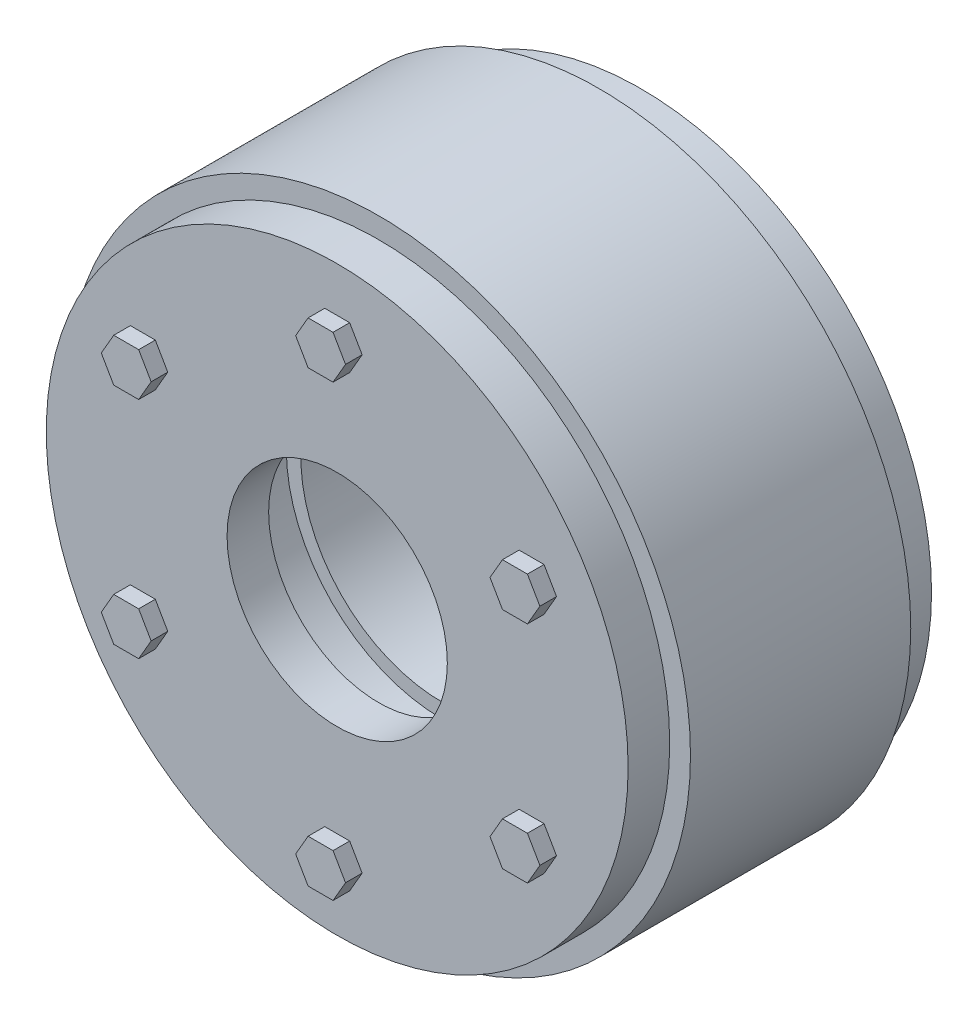
SolidWorks part; units mm, degrees
ref_plane "前视基准面" through (0, 0, 0) normal (0, 0, 1) x (1, 0, 0)
ref_plane "上视基准面" through (0, 0, 0) normal (0, 1, 0) x (1, 0, 0)
ref_plane "右视基准面" through (0, 0, 0) normal (1, 0, 0) x (0, 0, -1)
sketch "草图1" plane through (0, 0, 0) normal (0, 1, 0) x (1, 0, 0)
  line L0 (37.5, 26.5) -> (37.5, 11.25)
  line L1 (37.5, 11.25) -> (34, 11.25)
  line L2 (34, 11.25) -> (34, -11.25)
  line L3 (34, -11.25) -> (37.5, -11.25)
  line L4 (37.5, -11.25) -> (37.5, -26.5)
  line L5 (37.5, -26.5) -> (75, -26.5)
  line L6 (75, -26.5) -> (75, 26.5)
  line L7 (75, 26.5) -> (37.5, 26.5)
  line L8 (-1000, 0) -> (49000, 0) construction
  line L9 (0, -1000) -> (0, 49000) construction
  dimension "D1" = 34
  dimension "D2" = 22.5
  dimension "D3" = 37.5
  dimension "D4" = 53
  dimension "D5" = 75
revolve "旋转1" add sketch "草图1" angle 360 about L9
sketch "草图2" plane through (0, 0, 26.5) normal (0, 0, 1) x (1, 0, 0)
  circle A0 centre (0, 0) radius 34.5
  circle A1 centre (0, 0) radius 37.5
  circle A2 centre (0, 0) radius 37.5 construction
  dimension "D1" = 69
extrude "凸台-拉伸1" add sketch "草图2" against normal blind 3
sketch "草图3" plane through (0, 0, 26.5) normal (0, 0, 1) x (1, 0, 0)
  circle A0 centre (0, 0) radius 70
  circle A1 centre (0, 0) radius 26.5
  circle A2 centre (0, 0) radius 34 construction
  dimension "D1" = 140
  dimension "D2" = 53
extrude "凸台-拉伸2" add sketch "草图3" along normal blind 10
sketch "草图4" plane through (0, 0, 0) normal (1, 0, 0) x (0, 0, -1)
  line L0 (-1000, 0) -> (49000, 0) construction
  line L1 (26.5, 37.5) -> (26.5, 70)
  line L2 (26.5, -75) -> (26.5, 75) construction
  line L3 (26.5, 70) -> (36.5, 70)
  line L4 (36.5, 70) -> (36.5, 45.6421)
  line L5 (26.5, 37.5) -> (24.5, 37.5)
  line L6 (24.5, 37.5) -> (24.5, 34.5)
  line L7 (24.5, 34.5) -> (28.5, 34.5)
  line L8 (38.5, 24.5) -> (38.5, 18.5)
  line L9 (38.5, 18.5) -> (46.5, 18.5)
  line L10 (46.5, 18.5) -> (46.5, 31.5)
  arc A0 (38.5, 24.5) -> (28.5, 34.5) centre (28.5, 24.5) ccw
  arc A1 (46.5, 31.5) -> (39.8333, 40.9281) centre (36.5, 31.5) ccw
  arc A2 (39.8333, 40.9281) -> (36.5, 45.6421) centre (41.5, 45.6421) cw
  dimension "D8" = 10
  dimension "D9" = 10
  dimension "D11" = 5
  dimension "D1" = 70
  dimension "D2" = 37.5
  dimension "D3" = 2
  dimension "D4" = 34.5
  dimension "D5" = 18.5
  dimension "D6" = 14
  dimension "D7" = 22
  dimension "D10" = 10
  dimension "D12" = 31.5
revolve "旋转2" add sketch "草图4" angle 360 about L0
sketch "草图5" plane through (0, 0, 36.5) normal (0, 0, 1) x (1, 0, 0)
  line L0 (0, -1000) -> (0, 49000) construction
  line L2 (3, 48.8038) -> (6, 54)
  line L3 (6, 54) -> (3, 59.1962)
  line L4 (3, 59.1962) -> (-3, 59.1962)
  line L5 (-3, 59.1962) -> (-6, 54)
  line L6 (-6, 54) -> (-3, 48.8038)
  line L7 (-3, 48.8038) -> (3, 48.8038)
  circle A0 centre (0, 54) radius 5.1962 construction
  dimension "D1" = 6
  dimension "D2" = 54
extrude "凸台-拉伸3" add sketch "草图5" along normal blind 4
pattern_circular "阵列(圆周)1" count 6 over 360 about axis through (0, 0, 0) along (0, 0, 1) of "凸台-拉伸3"
pattern_linear "阵列(线性)1" count 2 spacing 77 along (0, 0, -1) of "阵列(圆周)1", "凸台-拉伸3"
